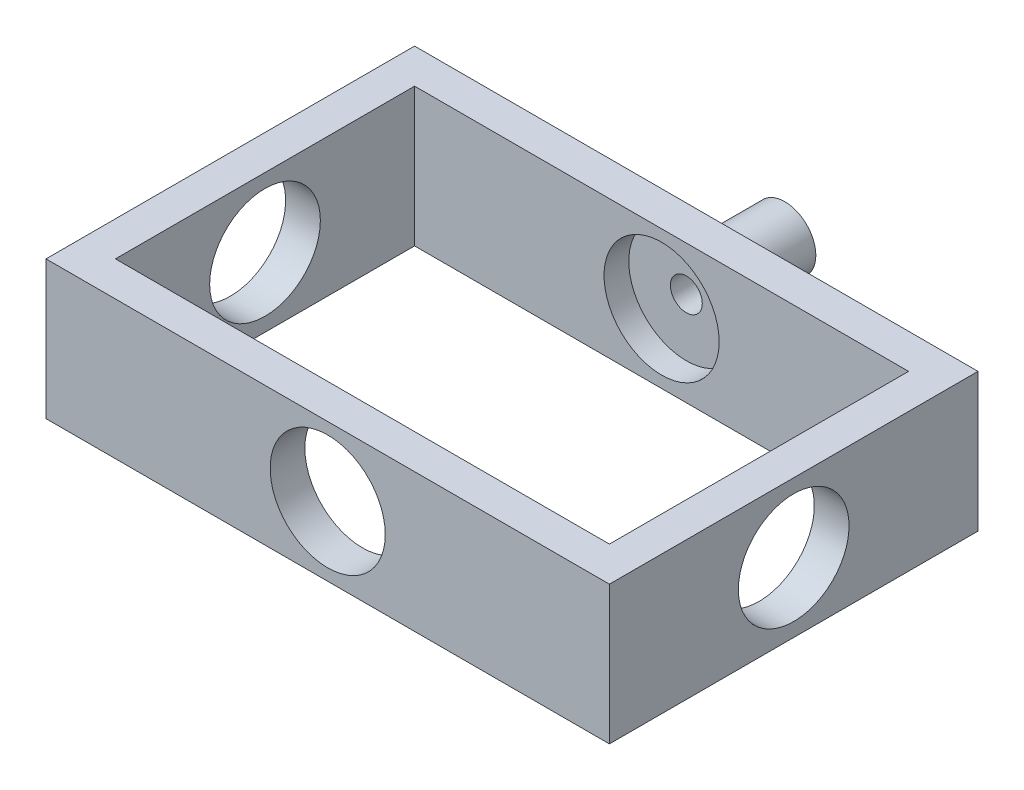
SolidWorks part; units mm, degrees
ref_plane "Front Plane" through (0, 0, 0) normal (0, 0, 1) x (1, 0, 0)
ref_plane "Top Plane" through (0, 0, 0) normal (0, 1, 0) x (1, 0, 0)
ref_plane "Right Plane" through (0, 0, 0) normal (1, 0, 0) x (0, 0, -1)
sketch "Sketch1" plane through (0, 0, 0) normal (0, 1, 0) x (1, 0, 0)
  line L1 (-16.1608, 10.5727) -> (16.1607, 10.5727)
  line L2 (-16.1608, 10.5727) -> (-16.1607, -10.5728)
  line L3 (-16.1607, -10.5728) -> (16.1607, -10.5728)
  line L4 (16.1607, 10.5727) -> (16.1607, -10.5728)
  line L5 (-16.1608, 10.5727) -> (16.1607, -10.5728) construction
  line L6 (-16.1607, -10.5728) -> (16.1607, 10.5727) construction
  line L7 (-14.1694, 8.5814) -> (14.1694, 8.5814)
  line L8 (-14.1694, 8.5814) -> (-14.1694, -8.5814)
  line L9 (-14.1694, -8.5814) -> (14.1694, -8.5814)
  line L10 (14.1694, 8.5814) -> (14.1694, -8.5814)
  line L11 (-14.1694, 8.5814) -> (14.1694, -8.5814) construction
  line L12 (-14.1694, -8.5814) -> (14.1694, 8.5814) construction
  point P0 (0, 0)
  point P5 (0, 0)
extrude "Boss-Extrude1" add sketch "Sketch1" along normal blind 7.9375
sketch "Sketch2" plane through (-16.1608, 0, 0) normal (-1, 0, 0) x (0, 0, 1)
  circle A0 centre (0, 3.9688) radius 3.175
extrude "Cut-Extrude1" cut sketch "Sketch2" against normal blind 37.1475
sketch "Sketch3" plane through (0, 0, 10.5728) normal (0, 0, 1) x (1, 0, 0)
  circle A0 centre (0, 3.9688) radius 3.302
extrude "Cut-Extrude2" cut sketch "Sketch3" against normal blind 20.574
sketch "Sketch4" plane through (0, 0, -10.5727) normal (0, 0, -1) x (-1, 0, 0)
  circle A1 centre (0, 3.9688) radius 1.778
extrude "Boss-Extrude3" add sketch "Sketch4" along normal blind 5.08
sketch "Sketch6" plane through (0, 0, -15.6527) normal (0, 0, -1) x (-1, 0, 0)
  circle A0 centre (0, 3.9688) radius 0.9144
extrude "Cut-Extrude3" cut sketch "Sketch6" against normal blind 10.922
